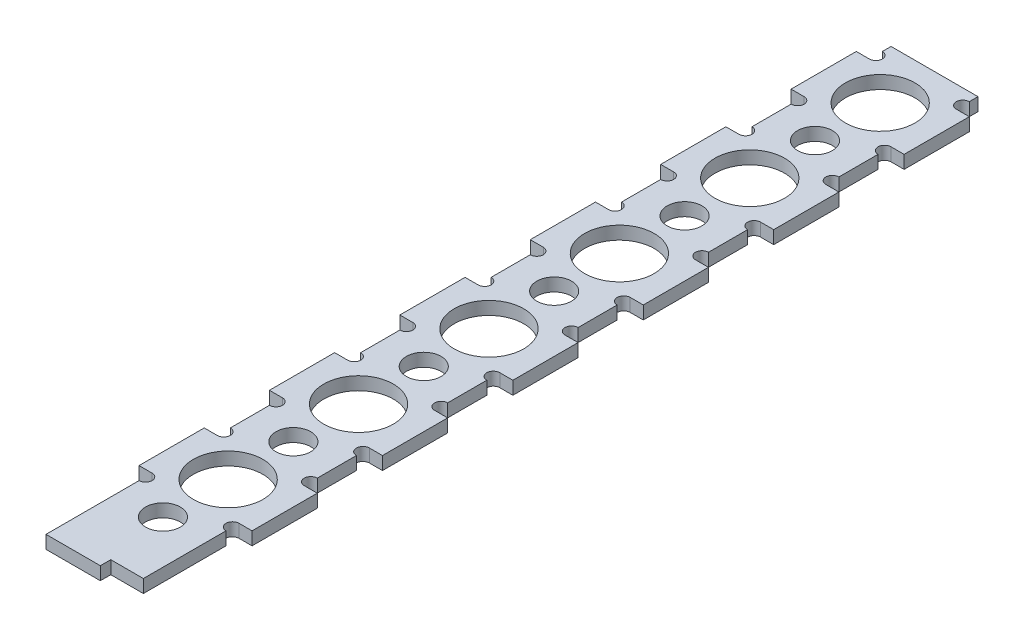
SolidWorks part; units mm, degrees
material "Thornel Mat VMA"
ref_plane "前视基准面" through (0, 0, 0) normal (0, 0, 1) x (1, 0, 0)
ref_plane "上视基准面" through (0, 0, 0) normal (0, 1, 0) x (1, 0, 0)
ref_plane "右视基准面" through (0, 0, 0) normal (1, 0, 0) x (0, 0, -1)
sketch "草图1" plane through (0, 0, 0) normal (0, 1, 0) x (1, 0, 0)
  line L1 (0, 0) -> (20, 0)
  line L2 (0, 0) -> (0, 194.9)
  line L3 (0, 194.9) -> (20, 194.9)
  line L4 (20, 0) -> (20, 194.9)
  dimension "D1" = 20
  dimension "D2" = 194.9
extrude "凸台-拉伸1" add sketch "草图1" along normal blind 3
sketch "草图2" plane through (0, 3, 0) normal (0, 1, 0) x (1, 0, 0)
  line L0 (20, 0) -> (20, 194.9) construction
  line L2 (20, 0) -> (12.5, 0)
  line L3 (20, 0) -> (20, 2.9)
  line L4 (20, 2.9) -> (12.5, 2.9)
  line L5 (12.5, 0) -> (12.5, 2.9)
  dimension "D1" = 2.9
  dimension "D2" = 7.5
extrude "切除-拉伸1" cut sketch "草图2" against normal through all
sketch "草图3" plane through (0, 0, 0) normal (-1, 0, 0) x (0, 0, 1)
  line L0 (-194.9, 3) -> (0, 3) construction
  line L1 (-189.9, 3) -> (-174.9, 3)
  line L2 (-189.9, 3) -> (-189.9, 0)
  line L3 (-189.9, 0) -> (-174.9, 0)
  line L4 (-174.9, 3) -> (-174.9, 0)
  line L5 (-194.9, 0) -> (0, 0) construction
  line L6 (-194.9, 3) -> (-194.9, 0) construction
  line L7 (-159.9, 3) -> (-159.9, 0)
  line L8 (-159.9, 3) -> (-144.9, 3)
  line L9 (-144.9, 3) -> (-144.9, 0)
  line L10 (-159.9, 0) -> (-144.9, 0)
  line L11 (-129.9, 3) -> (-129.9, 0)
  line L12 (-129.9, 3) -> (-114.9, 3)
  line L13 (-114.9, 3) -> (-114.9, 0)
  line L14 (-129.9, 0) -> (-114.9, 0)
  line L15 (-99.9, 3) -> (-99.9, 0)
  line L16 (-99.9, 3) -> (-84.9, 3)
  line L17 (-84.9, 3) -> (-84.9, 0)
  line L18 (-99.9, 0) -> (-84.9, 0)
  line L19 (-69.9, 3) -> (-69.9, 0)
  line L20 (-69.9, 3) -> (-54.9, 3)
  line L21 (-54.9, 3) -> (-54.9, 0)
  line L22 (-69.9, 0) -> (-54.9, 0)
  line L23 (-39.9, 3) -> (-39.9, 0)
  line L24 (-39.9, 3) -> (-24.9, 3)
  line L25 (-24.9, 3) -> (-24.9, 0)
  line L26 (-39.9, 0) -> (-24.9, 0)
  dimension "D1" = 5
  dimension "D2" = 15
  dimension "D3" = 6
extrude "凸台-拉伸3" add sketch "草图3" along normal blind 3
ref_plane "基准面1" through (10, 0, 0) normal (-1, 0, 0) x (0, 0, 1)
mirror "镜向1" about plane through (10, 0, 0) normal (-1, 0, 0) of "凸台-拉伸3"
sketch "草图4" plane through (0, 3, 0) normal (0, 1, 0) x (1, 0, 0)
  line L0 (20, 194.9) -> (0, 194.9) construction
  line L1 (10, 194.9) -> (10, 15.5124) construction
  circle A0 centre (10, 182.4) radius 8
  circle A1 centre (10, 152.4) radius 8
  circle A2 centre (10, 122.4) radius 8
  circle A3 centre (10, 92.4) radius 8
  circle A4 centre (10, 62.4) radius 8
  circle A5 centre (10, 32.4) radius 8
  dimension "D1" = 16
  dimension "D2" = 12.5
  dimension "D3" = 6
extrude "切除-拉伸2" cut sketch "草图4" against normal through all
sketch "草图5" plane through (0, 3, 0) normal (0, 1, 0) x (1, 0, 0)
  line L0 (10, 174.4) -> (10, 160.4) construction
  circle A0 centre (10, 182.4) radius 8 construction
  circle A1 centre (10, 152.4) radius 8 construction
  circle A2 centre (10, 167.4) radius 4
  circle A3 centre (10, 137.4) radius 4
  circle A4 centre (10, 107.4) radius 4
  circle A5 centre (10, 77.4) radius 4
  circle A6 centre (10, 47.4) radius 4
  circle A7 centre (10, 17.4) radius 4
  dimension "D1" = 8
  dimension "D2" = 6
extrude "切除-拉伸3" cut sketch "草图5" against normal through all
sketch "草图6" plane through (0, 3, 0) normal (0, 1, 0) x (1, 0, 0)
  line L0 (12.5, 2.9) -> (12.5, 0) construction
  line L1 (0, 0) -> (12.5, 0)
  line L2 (0, 0) -> (0, 0.5)
  line L3 (0, 0.5) -> (12.5, 0.5)
  line L4 (12.5, 0) -> (12.5, 0.5)
  dimension "D1" = 0.5
extrude "切除-拉伸4" cut sketch "草图6" against normal through all
sketch "草图7" plane through (0, 0, 0) normal (0, -1, 0) x (1, 0, 0)
  line L0 (10, -40.4) -> (10, -24.4) construction
  line L1 (0, -24.9) -> (0, -0.5) construction
  line L2 (0, -54.9) -> (0, -39.9) construction
  line L3 (0, -84.9) -> (0, -69.9) construction
  line L4 (0, -114.9) -> (0, -99.9) construction
  line L5 (0, -144.9) -> (0, -129.9) construction
  line L6 (0, -174.9) -> (0, -159.9) construction
  line L7 (0, -194.9) -> (0, -189.9) construction
  line L8 (-3, -189.9) -> (0, -189.9) construction
  line L9 (-3, -174.9) -> (0, -174.9) construction
  line L10 (-3, -159.9) -> (0, -159.9) construction
  line L11 (-3, -144.9) -> (0, -144.9) construction
  line L12 (-3, -129.9) -> (0, -129.9) construction
  line L13 (-3, -114.9) -> (0, -114.9) construction
  line L14 (-3, -99.9) -> (0, -99.9) construction
  line L15 (-3, -84.9) -> (0, -84.9) construction
  line L16 (-3, -69.9) -> (0, -69.9) construction
  line L17 (-3, -54.9) -> (0, -54.9) construction
  line L18 (-3, -39.9) -> (0, -39.9) construction
  line L19 (-3, -24.9) -> (0, -24.9) construction
  circle A0 centre (10, -32.4) radius 8 construction
  circle A1 centre (0, -23.4) radius 1.5
  circle A2 centre (0, -41.4) radius 1.5
  circle A3 centre (0, -53.4) radius 1.5
  circle A4 centre (0, -71.4) radius 1.5
  circle A5 centre (0, -83.4) radius 1.5
  circle A6 centre (0, -101.4) radius 1.5
  circle A7 centre (0, -113.4) radius 1.5
  circle A8 centre (0, -131.4) radius 1.5
  circle A9 centre (0, -143.4) radius 1.5
  circle A10 centre (0, -161.4) radius 1.5
  circle A11 centre (0, -173.4) radius 1.5
  circle A12 centre (0, -191.4) radius 1.5
  circle A13 centre (20, -191.4) radius 1.5
  circle A14 centre (20, -173.4) radius 1.5
  circle A15 centre (20, -161.4) radius 1.5
  circle A16 centre (20, -143.4) radius 1.5
  circle A17 centre (20, -131.4) radius 1.5
  circle A18 centre (20, -113.4) radius 1.5
  circle A19 centre (20, -101.4) radius 1.5
  circle A20 centre (20, -83.4) radius 1.5
  circle A21 centre (20, -71.4) radius 1.5
  circle A22 centre (20, -53.4) radius 1.5
  circle A23 centre (20, -41.4) radius 1.5
  circle A24 centre (20, -23.4) radius 1.5
  dimension "D1" = 3
  dimension "D2" = 3
  dimension "D3" = 3
  dimension "D4" = 3
  dimension "D5" = 3
  dimension "D6" = 3
  dimension "D7" = 3
  dimension "D8" = 3
  dimension "D9" = 3
  dimension "D10" = 3
  dimension "D11" = 3
  dimension "D12" = 3
  dimension "D13" = 1.5
  dimension "D14" = 1.5
  dimension "D16" = 1.5
  dimension "D17" = 1.5
  dimension "D18" = 1.5
  dimension "D19" = 1.5
  dimension "D20" = 1.5
  dimension "D21" = 1.5
  dimension "D22" = 1.5
  dimension "D23" = 1.5
  dimension "D24" = 1.5
  dimension "D15" = 1.5
extrude "切除-拉伸5" cut sketch "草图7" against normal blind 10
